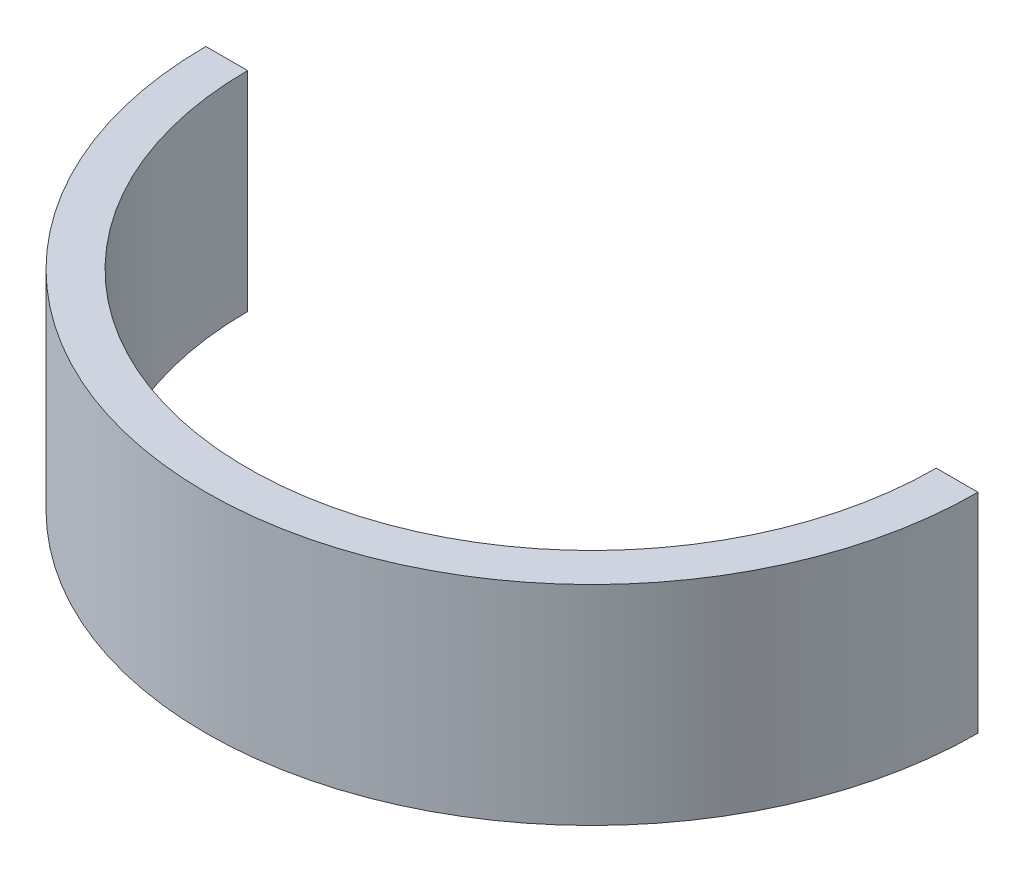
SolidWorks part; units mm, degrees
ref_plane "Front" through (0, 0, 0) normal (0, 0, 1) x (1, 0, 0)
ref_plane "Top" through (0, 0, 0) normal (0, 1, 0) x (1, 0, 0)
ref_plane "Right" through (0, 0, 0) normal (1, 0, 0) x (0, 0, -1)
sketch "草图1" plane through (0, 0, 0) normal (0, 1, 0) x (1, 0, 0)
  line L0 (-74, 0) -> (-66, 0)
  line L1 (66, 0) -> (74, 0)
  arc A0 (-74, 0) -> (74, 0) centre (0, 0) ccw
  arc A1 (-66, 0) -> (66, 0) centre (0, 0) ccw
extrude "凸台-拉伸1" add sketch "草图1" along normal blind 40
